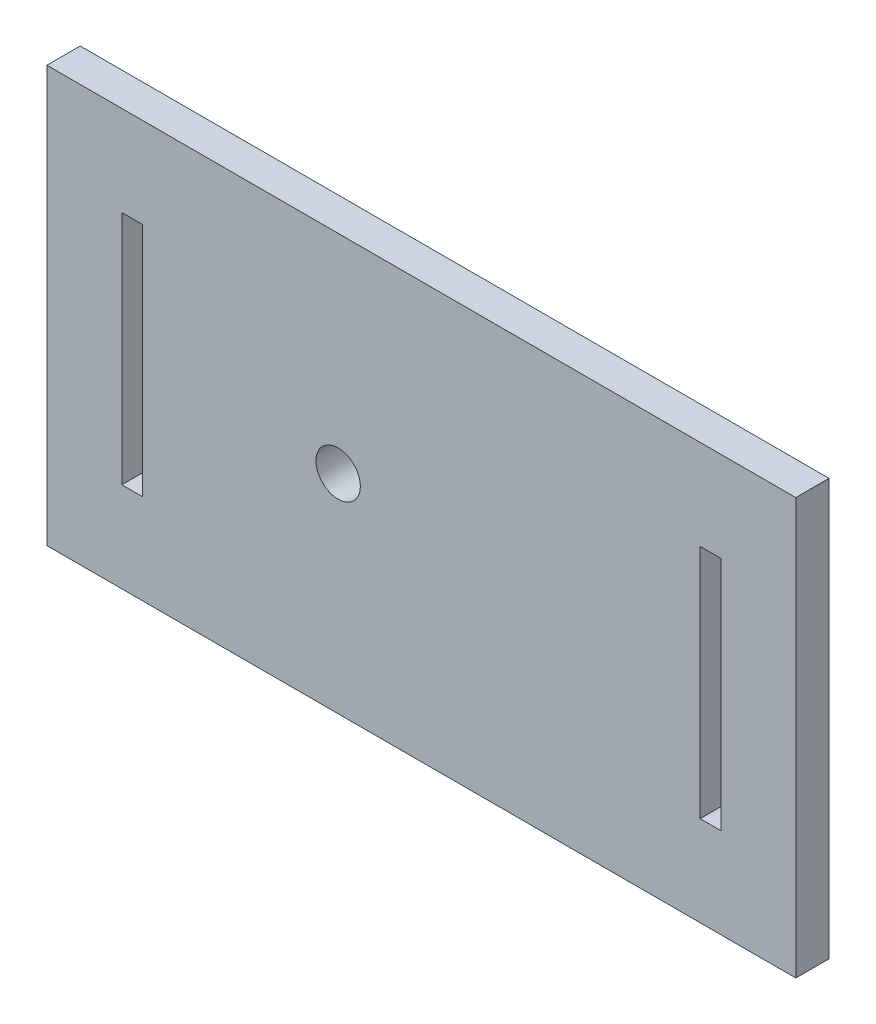
SolidWorks part; units mm, degrees
ref_plane "Front Plane" through (0, 0, 0) normal (0, 0, 1) x (1, 0, 0)
ref_plane "Top Plane" through (0, 0, 0) normal (0, 1, 0) x (1, 0, 0)
ref_plane "Right Plane" through (0, 0, 0) normal (1, 0, 0) x (0, 0, -1)
sketch "Sketch1" plane through (0, 0, 0) normal (0, 0, 1) x (1, 0, 0)
  line L0 (0, 15) -> (0, -15)
  line L1 (27, 15) -> (-27, 15)
  line L2 (27, 15) -> (27, -15)
  line L3 (27, -15) -> (-27, -15)
  line L4 (-27, 15) -> (-27, -15)
  line L5 (27, 15) -> (-27, -15) construction
  line L6 (27, -15) -> (-27, 15) construction
  line L7 (20.1, 8.5) -> (-20.1, 8.5)
  line L8 (20.1, 8.5) -> (20.1, -8.5)
  line L9 (20.1, -8.5) -> (-20.1, -8.5)
  line L10 (-20.1, 8.5) -> (-20.1, -8.5)
  line L11 (20.1, 8.5) -> (-20.1, -8.5) construction
  line L12 (20.1, -8.5) -> (-20.1, 8.5) construction
  line L13 (-20.1, 8.5) -> (-21.6, 8.5)
  line L14 (-20.1, 8.5) -> (-20.1, -8.5)
  line L15 (-20.1, -8.5) -> (-21.6, -8.5)
  line L16 (-21.6, 8.5) -> (-21.6, -8.5)
  line L17 (20.1, -8.5) -> (21.6, -8.5)
  line L18 (20.1, 8.5) -> (21.6, 8.5)
  line L19 (21.6, 8.5) -> (21.6, -8.5)
  line L20 (0, 0) -> (-6, 0)
  circle A1 centre (-6, 0) radius 1.6
  point P0 (0, 0)
  point P6 (0, 0)
extrude "Boss-Extrude1" add sketch "Sketch1" along normal blind 2.4 contours L16 L13 L7 L0 L1 L4 L3 L9 L15 | L7 L10 L9 L0 | L18 L19 L17 L9 L0 L3 L2 L1 L7 | L9 L8 L7 L0
